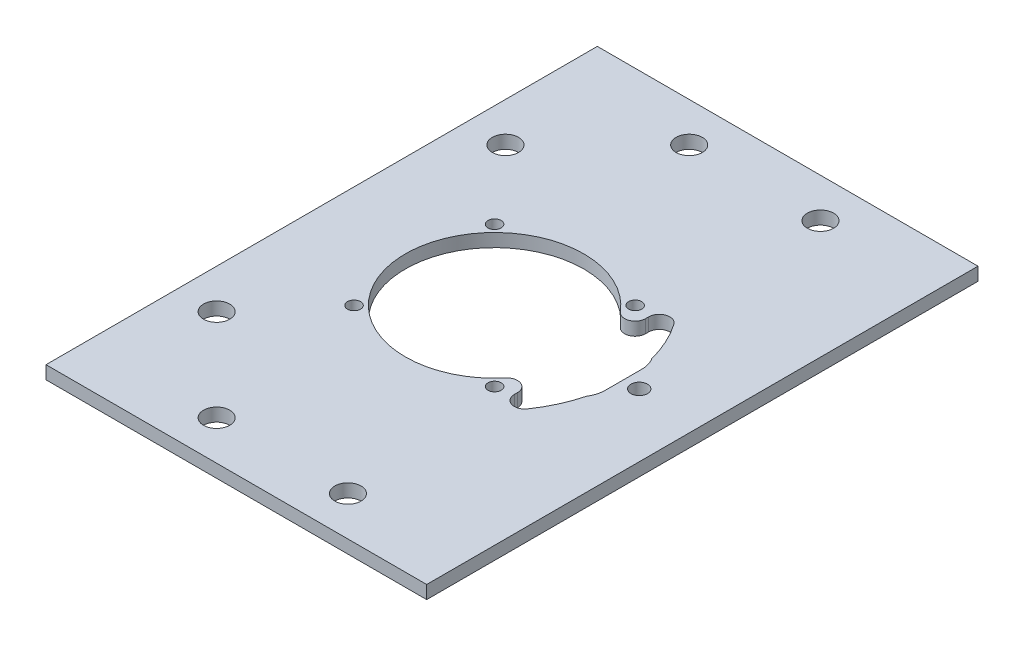
SolidWorks part; units mm, degrees
material "6061-T6 (SS)"
ref_plane "Front Plane" through (0, 0, 0) normal (0, 0, 1) x (1, 0, 0)
ref_plane "Top Plane" through (0, 0, 0) normal (0, 1, 0) x (1, 0, 0)
ref_plane "Right Plane" through (0, 0, 0) normal (1, 0, 0) x (0, 0, -1)
sketch "Sketch1" plane through (0, 0, 0) normal (0, 1, 0) x (1, 0, 0)
  line L1 (-95.25, -66.675) -> (95.25, -66.675)
  line L2 (-95.25, -66.675) -> (-95.25, 66.675)
  line L3 (-95.25, 66.675) -> (95.25, 66.675)
  line L4 (95.25, -66.675) -> (95.25, 66.675)
  line L5 (-95.25, -66.675) -> (95.25, 66.675) construction
  line L6 (-95.25, 66.675) -> (95.25, -66.675) construction
  point P0 (0, 0)
  dimension "D1" = 133.35
  dimension "D2" = 190.5
extrude "Boss-Extrude1" add sketch "Sketch1" along normal blind 3.175 contours L3 L4 L1 L2
sketch "Sketch3" plane through (0, 3.175, 0) normal (0, 1, 0) x (1, 0, 0)
  line L0 (-95.25, 0) -> (95.25, 0) construction
  line L1 (-95.25, -66.675) -> (-95.25, 66.675) construction
  line L2 (95.25, -66.675) -> (95.25, 66.675) construction
  circle A0 centre (-53.425, 0) radius 21.59
  dimension "D1" = 43.18
  dimension "D2" = 41.825
extrude "Cut-Extrude2" cut sketch "Sketch3" against normal through all
sketch "Sketch4" plane through (0, 3.175, 0) normal (0, 1, 0) x (1, 0, 0)
  line L0 (-70.425, 17) -> (-36.425, -17) construction
  line L5 (-53.425, 0) -> (22.4381, 0) construction
  line L6 (-70.425, 17) -> (-36.425, 17)
  line L7 (-53.425, 0) -> (-90.876, 0) construction
  line L8 (-70.425, 17) -> (-70.425, -17)
  line L9 (-70.425, -17) -> (-36.425, -17)
  line L10 (-36.425, 17) -> (-36.425, -17)
  line L11 (-36.425, 17) -> (-70.425, -17) construction
  line L12 (-36.425, 10.25) -> (-82.425, 10.25)
  circle A5 centre (-70.425, 17) radius 1.5875
  circle A6 centre (-36.425, 17) radius 1.5875
  circle A7 centre (-70.425, -17) radius 1.5875
  circle A8 centre (-36.425, -17) radius 1.5875
  circle A9 centre (-82.425, 10.25) radius 1.7
  circle A10 centre (-82.425, -10.25) radius 1.7
  circle A17 centre (-63.675, 29) radius 1.7
  circle A18 centre (-43.175, 29) radius 1.7
  circle A19 centre (-24.425, 10.25) radius 1.7
  circle A20 centre (-24.425, -10.25) radius 1.7
  circle A21 centre (-43.175, -29) radius 1.7
  circle A22 centre (-63.675, -29) radius 1.7
  point P10 (-53.425, 0)
  point P34 (-50.8425, 2.5825)
  point P47 (-53.425, 0)
  dimension "D8" = 3.4
  dimension "D9" = 3.175
  dimension "D10" = 4
  dimension "D1" = 3.175
  dimension "D5" = 6.75
  dimension "D7" = 3.4
  dimension "D11" = 3.175
  dimension "D12" = 3.175
  dimension "D2" = 34
  dimension "D3" = 34
  dimension "D4" = 0
  dimension "D6" = 12
extrude "Cut-Extrude3" cut sketch "Sketch4" against normal up to surface (3.175 mm away) up to face at (-53.425, 0, 21.59)
sketch "Sketch9" plane through (0, 3.175, 0) normal (0, 1, 0) x (1, 0, 0)
  line L4 (-95.25, 66.675) -> (-95.25, -66.675)
  line L20 (-95.25, 66.675) -> (-95.25, -66.675)
  line L24 (-95.25, -66.675) -> (95.25, -66.675)
  line L26 (-95.25, -66.675) -> (95.25, -66.675)
  line L28 (95.25, -66.675) -> (95.25, 66.675)
  line L29 (95.25, -66.675) -> (95.25, 66.675)
  line L30 (95.25, 66.675) -> (-95.25, 66.675)
  line L31 (95.25, 66.675) -> (-95.25, 66.675)
  circle A0 centre (-53.425, 0) radius 21.59 construction
  circle A1 centre (-53.425, 0) radius 21.59
  circle A6 centre (-18.4365, 0) radius 2
  dimension "D2" = 34.9885
  dimension "D3" = 4
  dimension "D1" = 0
extrude "Cut-Extrude5" cut sketch "Sketch9" against normal blind 10 contours A6
sketch "Sketch12" plane through (0, 3.175, 0) normal (0, 1, 0) x (1, 0, 0)
  line L0 (-95.25, 66.675) -> (95.25, 66.675) construction
  line L1 (-3.175, 66.675) -> (95.25, 66.675)
  line L2 (-3.175, 66.675) -> (-3.175, -66.675)
  line L3 (-3.175, -66.675) -> (95.25, -66.675)
  line L4 (95.25, 66.675) -> (95.25, -66.675)
  line L5 (-95.25, -66.675) -> (-95.25, 66.675) construction
  dimension "D1" = 92.075
extrude "Cut-Extrude6" cut sketch "Sketch12" against normal through all
sketch "Sketch13" plane through (0, 3.175, 0) normal (0, 1, 0) x (1, 0, 0)
  line L0 (-95.25, -66.675) -> (-3.175, -66.675) construction
  line L1 (-95.25, -66.675) -> (-95.25, 66.675) construction
  line L2 (-3.175, 66.675) -> (-3.175, -66.675) construction
  line L3 (-95.25, 0) -> (-3.175, 0) construction
  circle A0 centre (-63.5, -57.15) radius 3.175
  circle A1 centre (-31.75, -57.15) radius 3.175
  circle A2 centre (-85.725, -34.925) radius 3.175
  circle A3 centre (-85.725, 34.925) radius 3.175
  circle A4 centre (-31.75, 57.15) radius 3.175
  circle A5 centre (-63.5, 57.15) radius 3.175
  dimension "D1" = 6.35
  dimension "D4" = 6.35
  dimension "D6" = 6.35
  dimension "D2" = 9.525
  dimension "D3" = 31.75
  dimension "D5" = 31.75
  dimension "D7" = 31.75
  dimension "D8" = 9.525
  dimension "D9" = 0
extrude "Cut-Extrude7" cut sketch "Sketch13" against normal through all
sketch "Sketch14" plane through (0, 3.175, 0) normal (0, 1, 0) x (1, 0, 0)
  line L0 (-53.425, 0) -> (-34.7275, 10.795) construction
  line L1 (-53.425, 0) -> (-34.7275, -10.795) construction
  line L2 (-53.425, 0) -> (-36.425, -17) construction
  line L3 (-53.425, 0) -> (-36.425, 17) construction
  line L4 (-34.7275, 10.795) -> (-28.5965, 10.795)
  line L5 (-22.2465, 4.445) -> (-22.2465, -4.445)
  line L6 (-28.5965, -10.795) -> (-34.7275, -10.795)
  line L7 (-18.4365, 0) -> (-22.2465, 0) construction
  arc A1 (-34.7275, -10.795) -> (-34.7275, 10.795) centre (-53.425, 0) ccw
  arc A2 (-22.2465, -4.445) -> (-28.5965, -10.795) centre (-28.5965, -4.445) cw
  arc A3 (-28.5965, 10.795) -> (-22.2465, 4.445) centre (-28.5965, 4.445) cw
  point P15 (-22.2465, 10.795)
  circle M17 centre (-53.425, 0) radius 21.59
  dimension "D3" = 21.59
  dimension "D6" = 6.35
  dimension "D1" = 15
  dimension "D2" = 15
  dimension "D4" = 21.59
  dimension "D5" = 0
  dimension "D7" = 3.81
extrude "Cut-Extrude8" cut sketch "Sketch14" against normal through all contours A3 L4 L6 A2 L5 M17
sketch "Sketch15" plane through (0, 3.175, 0) normal (0, 1, 0) x (1, 0, 0)
  line L0 (-53.425, 0) -> (-95.25, 8.4598) construction
  line L1 (-95.25, -66.675) -> (-95.25, 66.675) construction
  line L2 (-53.425, 0) -> (-95.25, -8.4598) construction
  line L3 (-53.425, 0) -> (-114.1178, 0) construction
  circle A0 centre (-53.425, 0) radius 42.672
  dimension "D1" = 85.344
  dimension "D2" = 0
  dimension "D3" = 0
  dimension "D4" = 11.435
  dimension "D5" = 11.435
sketch "Sketch17" plane through (0, 3.175, 0) normal (0, 1, 0) x (1, 0, 0)
  line L0 (-34.7275, -10.795) -> (-22.2465, -4.445) construction
  line L1 (-22.2465, -4.445) -> (-22.2465, -10.795) construction
  line L2 (-34.7275, -10.795) -> (-22.2465, -10.795) construction
  line L3 (-27.6179, -2.5694) -> (-29.8421, -2.5694)
  line L4 (-31.835, 0) -> (-4.693, 0) construction
  line L5 (-34.7275, -10.795) -> (-28.5965, -10.795)
  line L6 (-34.7275, 10.795) -> (-22.2465, 10.795) construction
  line L7 (-22.2465, 4.445) -> (-22.2465, 10.795) construction
  line L8 (-34.7275, 10.795) -> (-22.2465, 4.445) construction
  line L9 (-34.7275, 10.795) -> (-28.5965, 10.795)
  line L10 (-27.6179, 2.5694) -> (-29.8421, 2.5694)
  arc A0 (-34.7275, -10.795) -> (-32.3246, -4.5716) centre (-53.425, 0) ccw
  arc A1 (-27.5928, -2.8209) -> (-27.6179, -2.5694) centre (-27.6179, -2.6964) ccw
  arc A2 (-29.8421, -2.5694) -> (-32.3246, -4.5716) centre (-29.8421, -5.1094) ccw
  arc A3 (-28.5965, -10.795) -> (-24.2859, -9.1078) centre (-28.5965, -4.445) ccw
  arc A4 (-28.5965, -10.795) -> (-22.2465, -4.445) centre (-28.5965, -4.445) ccw construction
  arc A5 (-28.5965, 10.795) -> (-24.2859, 9.1078) centre (-28.5965, 4.445) cw
  arc A6 (-29.8421, 2.5694) -> (-32.3246, 4.5716) centre (-29.8421, 5.1094) cw
  arc A7 (-27.5928, 2.8209) -> (-27.6179, 2.5694) centre (-27.6179, 2.6964) cw
  arc A8 (-34.7275, 10.795) -> (-32.3246, 4.5716) centre (-53.425, 0) cw
  spline S0 degree 3 poles (-24.2859, -9.1078) (-25.2964, -8.7021) (-27.4268, -8.424) (-31.4923, -5.2) (-29.5627, -3.2177) (-27.5928, -2.8209) knots 0.242965 0.242965 0.242965 0.242965 0.418906 0.719123 0.942604 0.942604 0.942604 0.942604
  spline S1 degree 3 poles (-24.2859, 9.1078) (-25.2964, 8.7021) (-27.4268, 8.424) (-31.4923, 5.2) (-29.5627, 3.2177) (-27.5928, 2.8209) knots 0.242965 0.242965 0.242965 0.242965 0.418906 0.719123 0.942604 0.942604 0.942604 0.942604
  dimension "D2" = 0.127
  dimension "D3" = 2.54
  dimension "D1" = 0
  dimension "D4" = 5.1388
extrude "Boss-Extrude2" add sketch "Sketch17" against normal up to surface (3.175 mm away) up to face at (-31.75, 0, 60.325)
fillet "Fillet1" radius 2.54 2 edges at (-24.2859, 1.5875, 9.1078) (-24.2859, 1.5875, -9.1078)
sketch "Sketch19" plane through (0, 3.175, 0) normal (0, 1, 0) x (1, 0, 0)
  line L0 (-51.325, -18.532) -> (-51.325, -20.31)
  line L1 (-50.635, -21) -> (-43.984, -21)
  line L2 (-43.294, -20.31) -> (-43.294, -18.2391)
  line L3 (-40.556, -18.2391) -> (-40.556, -20.31)
  line L4 (-39.866, -21) -> (-36.425, -21)
  line L5 (-32.425, -17) -> (-32.425, 31.3117)
  line L6 (-33.5966, 34.1401) -> (-39.4007, 39.9443)
  line L7 (-43.294, 39.7609) -> (-43.294, 41.8317)
  line L8 (-43.984, 42.5217) -> (-50.635, 42.5217)
  line L9 (-51.325, 41.8317) -> (-51.325, 39.468)
  line L10 (-55.525, 39.468) -> (-55.525, 41.8317)
  line L11 (-56.215, 42.5217) -> (-62.866, 42.5217)
  line L12 (-63.556, 41.8317) -> (-63.556, 39.7609)
  line L13 (-67.4493, 39.9443) -> (-73.2534, 34.1401)
  line L14 (-74.425, 31.3117) -> (-74.425, -17)
  line L15 (-70.425, -21) -> (-66.984, -21)
  line L16 (-66.294, -20.31) -> (-66.294, -18.2391)
  line L17 (-63.556, -18.2391) -> (-63.556, -20.31)
  line L18 (-62.866, -21) -> (-56.215, -21)
  line L19 (-55.525, -20.31) -> (-55.525, -18.532)
  circle A0 centre (15.9196, 76.5857) radius 2.45
  circle A1 centre (-70.425, -17) radius 2.45
  circle A2 centre (-36.425, -17) radius 2.45
  circle A3 centre (49.9196, 76.5857) radius 2.45
  arc A4 (-51.325, -18.532) -> (-55.525, -18.532) centre (-53.425, -18.532) ccw
  arc A5 (-51.325, -20.31) -> (-50.635, -21) centre (-50.635, -20.31) ccw
  arc A6 (-43.984, -21) -> (-43.294, -20.31) centre (-43.984, -20.31) ccw
  arc A7 (-40.556, -18.2391) -> (-43.294, -18.2391) centre (-41.925, -18.2391) ccw
  arc A8 (-40.556, -20.31) -> (-39.866, -21) centre (-39.866, -20.31) ccw
  arc A9 (-36.425, -21) -> (-32.425, -17) centre (-36.425, -17) ccw
  arc A10 (-32.425, 31.3117) -> (-33.5966, 34.1401) centre (-36.425, 31.3117) ccw
  arc A11 (-39.4007, 39.9443) -> (-40.571, 39.5584) centre (-39.8886, 39.4564) ccw
  arc A12 (-43.294, 39.7609) -> (-40.571, 39.5584) centre (-41.925, 39.7609) ccw
  arc A13 (-43.294, 41.8317) -> (-43.984, 42.5217) centre (-43.984, 41.8317) ccw
  arc A14 (-50.635, 42.5217) -> (-51.325, 41.8317) centre (-50.635, 41.8317) ccw
  arc A15 (-55.525, 39.468) -> (-51.325, 39.468) centre (-53.425, 39.468) ccw
  arc A16 (-55.525, 41.8317) -> (-56.215, 42.5217) centre (-56.215, 41.8317) ccw
  arc A17 (-62.866, 42.5217) -> (-63.556, 41.8317) centre (-62.866, 41.8317) ccw
  arc A18 (-66.279, 39.5584) -> (-63.556, 39.7609) centre (-64.925, 39.7609) ccw
  arc A19 (-66.279, 39.5584) -> (-67.4493, 39.9443) centre (-66.9614, 39.4564) ccw
  arc A20 (-73.2534, 34.1401) -> (-74.425, 31.3117) centre (-70.425, 31.3117) ccw
  arc A21 (-74.425, -17) -> (-70.425, -21) centre (-70.425, -17) ccw
  arc A22 (-66.984, -21) -> (-66.294, -20.31) centre (-66.984, -20.31) ccw
  arc A23 (-63.556, -18.2391) -> (-66.294, -18.2391) centre (-64.925, -18.2391) ccw
  arc A24 (-63.556, -20.31) -> (-62.866, -21) centre (-62.866, -20.31) ccw
  arc A25 (-56.215, -21) -> (-55.525, -20.31) centre (-56.215, -20.31) ccw
  circle A26 centre (-70.425, -17) radius 1.5875 construction
  circle A27 centre (-70.425, -17) radius 1.5875
  point P73 (0, 0)
  dimension "D1" = 0
sketch "Sketch20" plane through (0, 3.175, 0) normal (0, 1, 0) x (1, 0, 0)
  line L0 (-22.2465, 0) -> (-53.425, 0) construction
  line L2 (-32.425, -17) -> (-32.425, 31.3117) construction
  line L3 (-32.388, -16.2432) -> (-32.3246, -4.5716)
  line L10 (-32.388, 16.2432) -> (-32.3246, 4.5716)
  arc A0 (-27.757, -17.6989) -> (-27.757, 17.6989) centre (-53.425, 0) ccw
  arc A2 (-27.757, 17.6989) -> (-32.388, 16.2432) centre (-29.8481, 16.257) ccw
  arc A4 (-32.3246, 4.5716) -> (-32.3246, -4.5716) centre (-53.425, 0) cw
  arc A7 (-27.757, -17.6989) -> (-32.388, -16.2432) centre (-29.8481, -16.257) cw
  point P18 (-32.425, 23.0456)
  dimension "D2" = 2.54
extrude "Cut-Extrude9" cut sketch "Sketch20" against normal through all
fillet "Fillet2" radius 2.54 2 edges at (-32.3246, 1.5875, 4.5716) (-32.3246, 1.5875, -4.5716)
